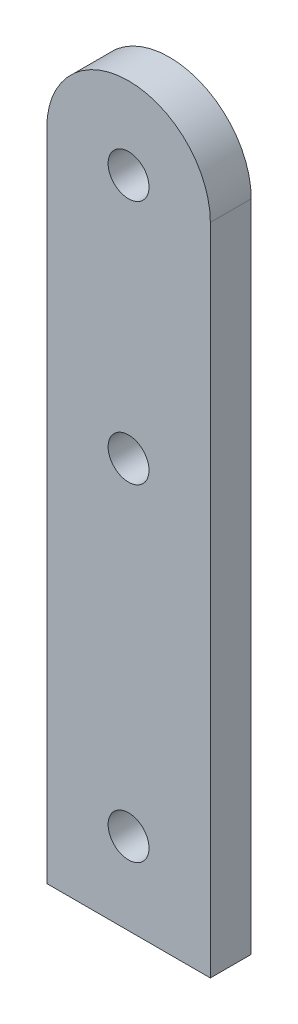
SolidWorks part; units mm, degrees
ref_plane "Front Plane" through (0, 0, 0) normal (0, 0, 1) x (1, 0, 0)
ref_plane "Top Plane" through (0, 0, 0) normal (0, 1, 0) x (1, 0, 0)
ref_plane "Right Plane" through (0, 0, 0) normal (1, 0, 0) x (0, 0, -1)
sketch "Sketch1" plane through (0, 0, 0) normal (0, 0, 1) x (1, 0, 0)
  line L0 (0, 0) -> (0, 101.6)
  line L1 (25.4, 101.6) -> (25.4, 0)
  line L2 (25.4, 0) -> (0, 0)
  arc A0 (0, 101.6) -> (25.4, 101.6) centre (12.7, 101.6) cw
  circle A1 centre (12.7, 101.6) radius 3.175
  dimension "D1" = 6.35
  dimension "D2" = 25.4
  dimension "D3" = 101.6
extrude "Boss-Extrude1" add sketch "Sketch1" along normal blind 6.35
sketch "Sketch2" plane through (0, 0, 6.35) normal (0, 0, 1) x (1, 0, 0)
  line L0 (12.7, 0) -> (12.7, 12.7) construction
  line L1 (0, 0) -> (25.4, 0) construction
  line L2 (12.7, 12.7) -> (12.7, 63.5) construction
  circle A0 centre (12.7, 63.5) radius 3.175
  circle A1 centre (12.7, 12.7) radius 3.175
  dimension "D1" = 6.35
  dimension "D2" = 50.8
  dimension "D3" = 12.7
extrude "Cut-Extrude1" cut sketch "Sketch2" against normal through all
